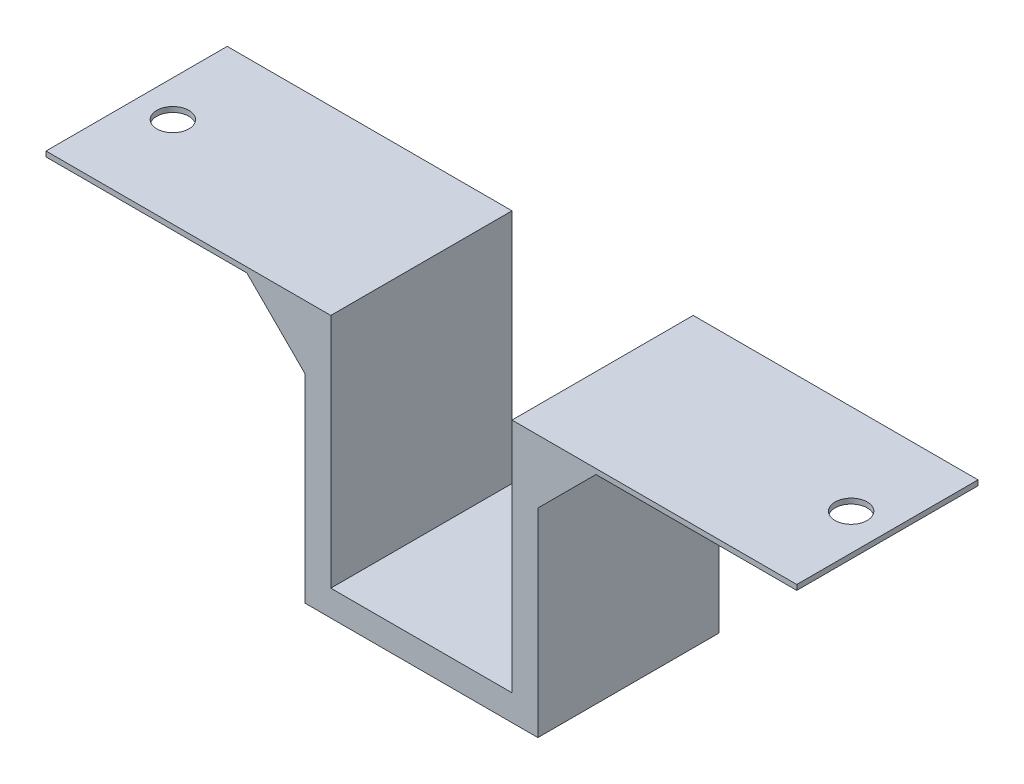
SolidWorks part; units mm, degrees
material "6061-T6 Aluminum"
ref_plane "Front Plane" through (0, 0, 0) normal (0, 0, 1) x (1, 0, 0)
ref_plane "Top Plane" through (0, 0, 0) normal (0, 1, 0) x (1, 0, 0)
ref_plane "Right Plane" through (0, 0, 0) normal (1, 0, 0) x (0, 0, -1)
sketch "Sketch1" plane through (0, 0, 0) normal (0, 0, 1) x (1, 0, 0)
  line L0 (-22.225, 0) -> (22.225, 0)
  line L1 (22.225, 0) -> (22.225, 57.9374)
  line L2 (22.225, 57.9374) -> (28.575, 57.9374)
  line L3 (28.575, 42.4243) -> (28.575, -6.35)
  line L4 (28.575, -6.35) -> (-28.575, -6.35)
  line L5 (-28.575, -6.35) -> (-28.575, 42.4243)
  line L6 (-22.225, 0) -> (-22.225, 57.9374)
  line L7 (-22.225, 57.9374) -> (-28.575, 57.9374)
  line L8 (-28.575, 57.9374) -> (-92.075, 57.9374)
  line L9 (-92.075, 57.9374) -> (-92.075, 56.6674)
  line L10 (-92.075, 56.6674) -> (-42.8181, 56.6674)
  line L11 (28.575, 57.9374) -> (92.075, 57.9374)
  line L12 (92.075, 57.9374) -> (92.075, 56.6674)
  line L13 (92.075, 56.6674) -> (42.8181, 56.6674)
  line L14 (-28.575, 56.6674) -> (-28.575, 57.9374) construction
  line L15 (28.575, 57.9374) -> (28.575, 56.6674) construction
  line L16 (-22.225, 0) -> (-28.575, 0) construction
  line L17 (22.225, 0) -> (28.575, 0) construction
  line L18 (-42.8181, 56.6674) -> (-28.575, 42.4243)
  line L19 (0, 0) -> (0, -6.35) construction
  line L20 (42.8181, 56.6674) -> (28.575, 42.4243)
  line L21 (-28.575, 42.4243) -> (-28.575, 56.6674) construction
  line L22 (-42.8181, 56.6674) -> (-28.575, 56.6674) construction
  line L23 (28.575, 56.6674) -> (28.575, 42.4243) construction
  line L24 (42.8181, 56.6674) -> (28.575, 56.6674) construction
  point P4 (0, 0)
  dimension "D1" = 44.45
  dimension "D2" = 57.9374
  dimension "D3" = 6.35
  dimension "D4" = 6.35
  dimension "D5" = 1.27
  dimension "D6" = 63.5
extrude "Boss-Extrude1" add sketch "Sketch1" along normal blind 44.45 contours L6 L7 L8 L9 L10 L18 L5 L4 L3 L20 L13 L12 L11 L2 L1 L0
sketch "Sketch2" plane through (0, 56.6674, 0) normal (0, -1, 0) x (1, 0, 0)
  line L0 (28.575, 22.225) -> (92.075, 22.225) construction
  line L1 (28.575, 44.45) -> (28.575, 0) construction
  line L2 (92.075, 44.45) -> (92.075, 0) construction
  line L3 (83.185, 0) -> (83.185, 44.45) construction
  line L4 (92.075, 44.45) -> (42.8181, 44.45) construction
  line L5 (0, 44.45) -> (0, 0) construction
  line L6 (28.575, 44.45) -> (-28.575, 44.45) construction
  line L7 (28.575, 0) -> (-28.575, 0) construction
  circle A0 centre (83.185, 22.225) radius 3.937
  circle A1 centre (-83.185, 22.225) radius 3.937
  point P11 (83.185, 22.225)
  dimension "D2" = 7.874
  dimension "D1" = 8.89
extrude "Cut-Extrude1" cut sketch "Sketch2" against normal through all
